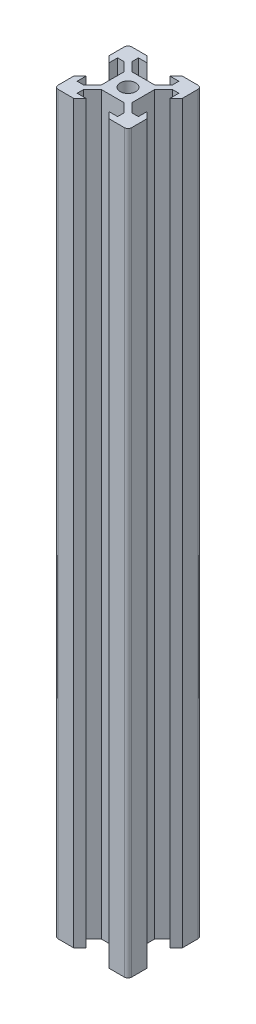
SolidWorks part; units mm, degrees
material "1060 Alloy"
ref_plane "Front Plane" through (0, 0, 0) normal (0, 0, 1) x (1, 0, 0)
ref_plane "Top Plane" through (0, 0, 0) normal (0, 1, 0) x (1, 0, 0)
ref_plane "Right Plane" through (0, 0, 0) normal (1, 0, 0) x (0, 0, -1)
ref_plane "End Plane" through (0, 200, 0) normal (0, 1, 0) x (1, 0, 0)
sketch "MasterLayoutSketch" plane through (0, 0, 0) normal (0, 1, 0) x (1, 0, 0)
  line L0 (-8.325, 3.1) -> (-8.325, 5.5)
  line L1 (-10, -10) -> (10, -10) construction
  line L2 (-10, -10) -> (-10, 10) construction
  line L3 (-10, 10) -> (10, 10) construction
  line L4 (10, -10) -> (10, 10) construction
  line L5 (-10, -10) -> (10, 10) construction
  line L6 (-10, 10) -> (10, -10) construction
  line L7 (-4.775, 10) -> (-3.1, 8.325)
  line L10 (-8.325, 5.5) -> (-6.5607, 5.5)
  line L11 (-10, 4.775) -> (-8.325, 3.1)
  line L12 (-5.5, 8.325) -> (-5.5, 6.5607)
  line L13 (-3.1, 8.325) -> (-5.5, 8.325)
  line L14 (-10, 10) -> (-10, 4.775)
  line L19 (3.1, 8.325) -> (5.5, 8.325)
  line L20 (10, 4.775) -> (8.325, 3.1)
  line L21 (-10, 10) -> (-4.775, 10)
  line L22 (-6.5607, 5.5) -> (-4.1607, 3.1)
  line L23 (-5.5, 6.5607) -> (-3.1, 4.1607)
  line L24 (5.5, 8.325) -> (5.5, 6.5607)
  line L25 (4.775, 10) -> (3.1, 8.325)
  line L26 (8.325, 5.5) -> (6.5607, 5.5)
  line L27 (8.325, 3.1) -> (8.325, 5.5)
  line L28 (10, 10) -> (4.775, 10)
  line L29 (10, 10) -> (10, 4.775)
  line L30 (5.5, 6.5607) -> (3.1, 4.1607)
  line L31 (6.5607, 5.5) -> (4.1607, 3.1)
  line L32 (8.325, -3.1) -> (8.325, -5.5)
  line L33 (4.775, -10) -> (3.1, -8.325)
  line L34 (8.325, -5.5) -> (6.5607, -5.5)
  line L35 (10, -4.775) -> (8.325, -3.1)
  line L36 (5.5, -8.325) -> (5.5, -6.5607)
  line L37 (3.1, -8.325) -> (5.5, -8.325)
  line L38 (10, -10) -> (10, -4.775)
  line L39 (10, -10) -> (4.775, -10)
  line L40 (6.5607, -5.5) -> (4.1607, -3.1)
  line L41 (5.5, -6.5607) -> (3.1, -4.1607)
  line L42 (-3.1, -8.325) -> (-5.5, -8.325)
  line L43 (-10, -4.775) -> (-8.325, -3.1)
  line L44 (-5.5, -8.325) -> (-5.5, -6.5607)
  line L45 (-4.775, -10) -> (-3.1, -8.325)
  line L46 (-8.325, -5.5) -> (-6.5607, -5.5)
  line L47 (-8.325, -3.1) -> (-8.325, -5.5)
  line L48 (-10, -10) -> (-4.775, -10)
  line L49 (-10, -10) -> (-10, -4.775)
  line L50 (-5.5, -6.5607) -> (-3.1, -4.1607)
  line L51 (-6.5607, -5.5) -> (-4.1607, -3.1)
  line L52 (-4.1607, 3.1) -> (-4.1607, -3.1)
  line L53 (-3.1, -4.1607) -> (3.1, -4.1607)
  line L54 (4.1607, -3.1) -> (4.1607, 3.1)
  line L55 (-3.1, 4.1607) -> (3.1, 4.1607)
  circle A0 centre (0, 0) radius 2.1
  point P0 (0, 0)
  point P9 (0, 0)
  dimension "D6" = 4.2
  dimension "D1" = 20
  dimension "D2" = 4
  dimension "D3" = 11
  dimension "D4" = 9.55
  dimension "D5" = 6.2
  dimension "D7" = 1.5
extrude "Main Extrusion" add sketch "MasterLayoutSketch" along normal up to surface (200 mm away) up to plane "End Plane"
fillet "Edge Fillets" radius 1 4 edges at (10, 100, -10) (10, 100, 10) (-10, 100, 10) (-10, 100, -10)
